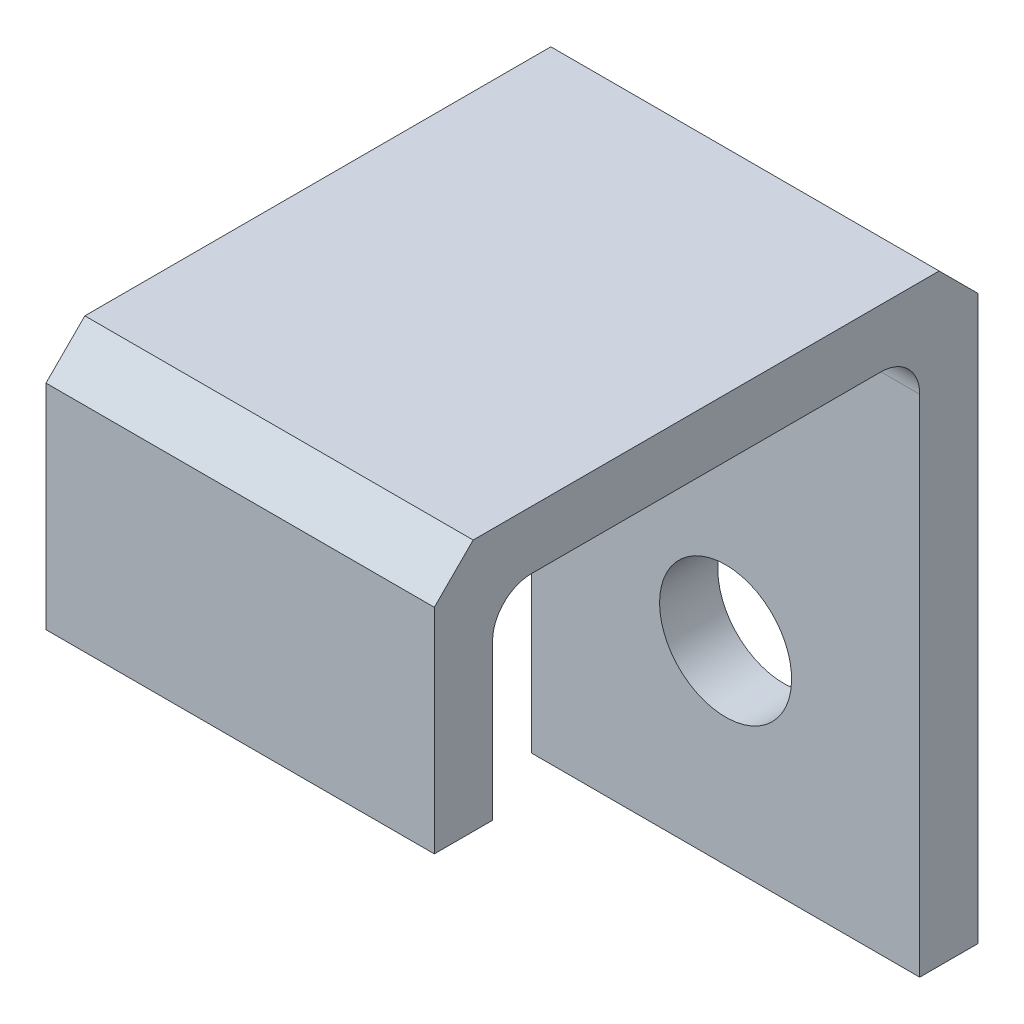
SolidWorks part; units mm, degrees
ref_plane "Front Plane" through (0, 0, 0) normal (0, 0, 1) x (1, 0, 0)
ref_plane "Top Plane" through (0, 0, 0) normal (0, 1, 0) x (1, 0, 0)
ref_plane "Right Plane" through (0, 0, 0) normal (1, 0, 0) x (0, 0, -1)
sketch "Sketch1" plane through (0, 0, 0) normal (1, 0, 0) x (0, 0, -1)
  line L0 (-2.1875, 6.5) -> (-3.1875, 5.5)
  line L1 (4.875, 6.5) -> (9.8125, 6.5)
  line L2 (9.3125, 4) -> (9.3125, -9)
  line L3 (9.3125, -9) -> (10.8125, -9)
  line L4 (10.8125, 5.5) -> (10.8125, -9)
  line L5 (4.875, 6.5) -> (-2.1875, 6.5)
  line L6 (9.8125, 6.5) -> (10.8125, 5.5)
  line L7 (8.3125, 5) -> (-0.6875, 5)
  line L8 (-3.1875, 5.5) -> (-3.1875, 5.2969)
  line L10 (-3.1875, 5.2969) -> (-3.1875, 0)
  line L11 (-3.1875, 0) -> (-1.6875, 0)
  line L12 (-1.6875, 4) -> (-1.6875, 0)
  arc A0 (9.3125, 4) -> (8.3125, 5) centre (8.3125, 4) ccw
  arc A1 (-0.6875, 5) -> (-1.6875, 4) centre (-0.6875, 4) ccw
  point P3 (10.8125, 6.5)
  point P6 (-3.1875, 6.5)
  dimension "D7" = 1
  dimension "D1" = 1.5
  dimension "D2" = 1.5
  dimension "D3" = 1.5
  dimension "D4" = 14
  dimension "D5" = 11
  dimension "D6" = 5
extrude "Boss-Extrude1" add sketch "Sketch1" along normal blind 10
sketch "Sketch2" plane through (0, 0, -10.8125) normal (0, 0, -1) x (-1, 0, 0)
  line L0 (-10, 5) -> (0, 5) construction
  circle A0 centre (-5, -4) radius 1.7
  dimension "D1" = 3.4
  dimension "D2" = 9
extrude "Cut-Extrude1" cut sketch "Sketch2" against normal blind 10
